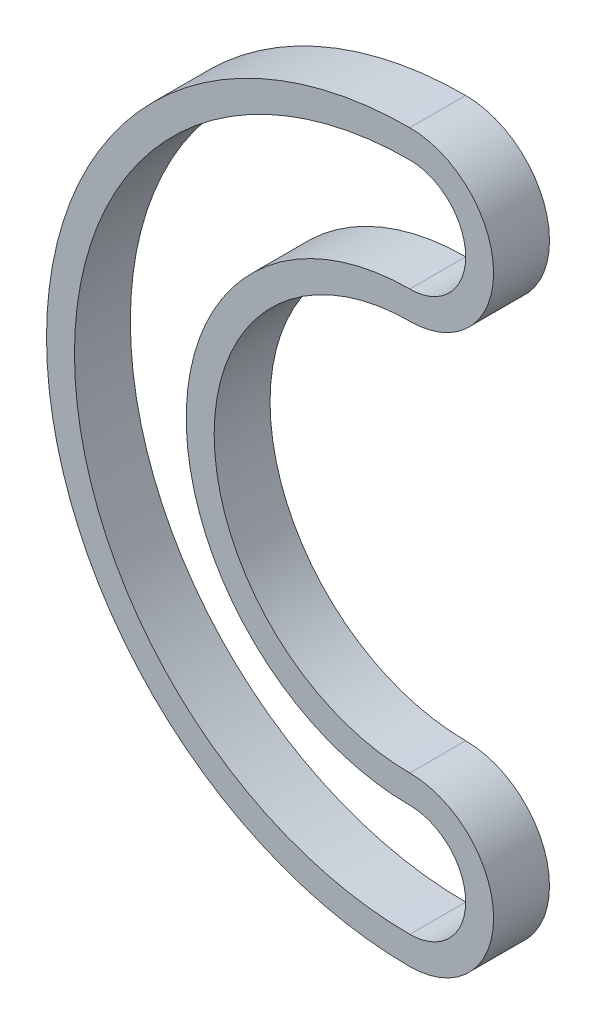
SolidWorks part; units mm, degrees
ref_plane "前视基准面" through (0, 0, 0) normal (0, 0, 1) x (1, 0, 0)
ref_plane "上视基准面" through (0, 0, 0) normal (0, 1, 0) x (1, 0, 0)
ref_plane "右视基准面" through (0, 0, 0) normal (1, 0, 0) x (0, 0, -1)
other "Configuration Table"
sketch "草图1" plane through (0, 0, 0) normal (0, 0, 1) x (1, 0, 0)
  line L4 (1.0247, 13.2335) -> (1.0247, 1.9198) construction
  line L5 (-0.9753, 11.5767) -> (-0.9753, 3.5767) construction
  arc A0 (-0.9753, 11.5767) -> (-0.9753, 3.5767) centre (-0.9753, 7.5767) ccw
  arc A1 (-0.9753, 13.5767) -> (-0.9753, 1.5767) centre (-0.9753, 7.5767) ccw
  arc A2 (1.0247, 13.2335) -> (1.0247, 1.9198) centre (-0.9753, 7.5767) ccw construction
  arc A3 (-0.9753, 11.5767) -> (-0.9753, 13.5767) centre (-0.9753, 12.5767) ccw
  arc A4 (-0.9753, 1.5767) -> (-0.9753, 3.5767) centre (-0.9753, 2.5767) ccw
  arc A5 (-0.9753, 11.0767) -> (-0.9753, 4.0767) centre (-0.9753, 7.5767) ccw
  arc A6 (-0.9753, 1.0767) -> (-0.9753, 4.0767) centre (-0.9753, 2.5767) ccw
  arc A7 (-0.9753, 14.0767) -> (-0.9753, 1.0767) centre (-0.9753, 7.5767) ccw
  arc A8 (-0.9753, 11.0767) -> (-0.9753, 14.0767) centre (-0.9753, 12.5767) ccw
  point P8 (0, 0)
  dimension "D1" = 8
  dimension "D3" = 2
  dimension "D4" = 2
  dimension "D5" = 0.5
  dimension "D2" = 2
extrude "凸台-拉伸1" add sketch "草图1" along normal mid plane 1
